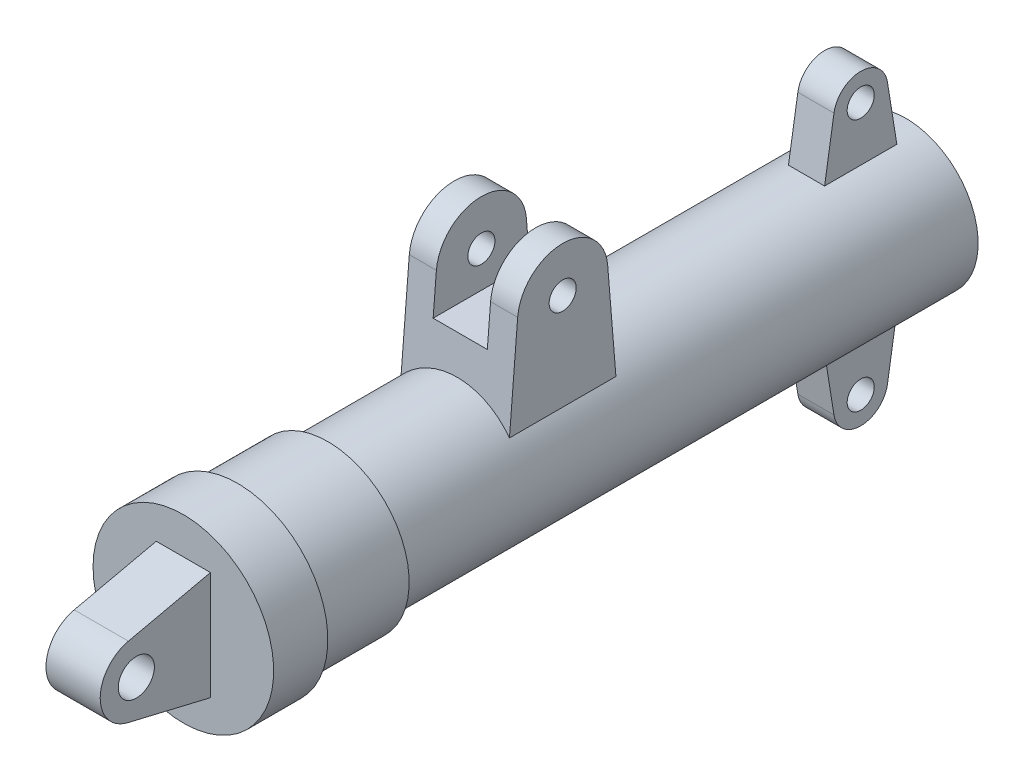
SolidWorks part; units mm, degrees
ref_plane "Front Plane" through (0, 0, 0) normal (1, 0, 0) x (0, 1, 0)
ref_plane "Top Plane" through (0, 0, 0) normal (0, 0, 1) x (0, 1, 0)
ref_plane "Right Plane" through (0, 0, 0) normal (0, 1, 0) x (-1, 0, 0)
sketch "Sketch1" plane through (0, 0, 0) normal (1, 0, 0) x (0, 1, 0)
  line L0 (0, -48.0597) -> (0, 85.8209) construction
  line L1 (0, -48.0597) -> (119.5522, -48.0597) construction
  line L2 (0, 336.9403) -> (0, 351.9403)
  line L3 (0, 351.9403) -> (50, 351.9403)
  line L4 (50, 351.9403) -> (50, 321.9403)
  line L5 (50, 321.9403) -> (45, 321.9403)
  line L6 (45, 321.9403) -> (45, 271.9403)
  line L7 (45, 271.9403) -> (40, 271.9403)
  line L8 (40, 271.9403) -> (40, -48.0597)
  line L9 (40, -48.0597) -> (22.5, -48.0597)
  line L10 (22.5, -48.0597) -> (22.5, -43.0597)
  line L11 (22.5, -43.0597) -> (35, -43.0597)
  line L12 (35, -43.0597) -> (35, 336.9403)
  line L13 (35, 336.9403) -> (0, 336.9403)
  dimension "D1" = 50
  dimension "D2" = 400
  dimension "D3" = 30
  dimension "D4" = 80
  dimension "D5" = 5
  dimension "D6" = 15
  dimension "D7" = 35
  dimension "D8" = 40
  dimension "D9" = 5
  dimension "D10" = 22.5
revolve "Revolve1" add sketch "Sketch1" angle 360 about L2
sketch "Sketch3" plane through (0, 0, 0) normal (1, 0, 0) x (0, 1, 0)
  line L0 (-50, 351.9403) -> (92.7072, 351.9403) construction
  line L1 (0, 310.0004) -> (0, 475.9652) construction
  line L2 (29.6972, 351.9403) -> (-30.3028, 351.9403)
  line L3 (-30.3028, 351.9403) -> (-19.4588, 397.6038)
  line L4 (29.6972, 351.9403) -> (19.5156, 397.3577)
  circle A0 centre (0, 392.9828) radius 10
  arc A1 (19.5156, 397.3577) -> (-19.4588, 397.6038) centre (0, 392.9828) ccw
  point P12 (-0.3028, 351.9403)
  dimension "D1" = 20
  dimension "D2" = 40
  dimension "D3" = 30
extrude "Boss-Extrude1" add sketch "Sketch3" along normal mid plane 30
sketch "Sketch4" plane through (0, 0, 0) normal (1, 0, 0) x (0, 1, 0)
  line L0 (-68.8038, -13.0597) -> (55, -13.0597) construction
  line L1 (0, -61.8196) -> (0, 86.7533) construction
  line L2 (1.3593, -48.0597) -> (76.4747, -48.0597) construction
  line L3 (-40, -48.0597) -> (40, -48.0597) construction
  line L4 (30, -33.0597) -> (30, 6.9403)
  line L5 (30, -33.0597) -> (0, -33.0597) construction
  line L6 (40, -13.0597) -> (40, -18.8653) construction
  line L7 (40, -48.0597) -> (40, 271.9403) construction
  line L8 (40, -13.0597) -> (40, 6.9403) construction
  line L9 (40, 6.9403) -> (40, -33.0597) construction
  line L10 (62.5, -13.0597) -> (95.0236, -13.0597) construction
  line L11 (40, 6.9403) -> (72.374, 1.7512)
  line L12 (40, 6.9403) -> (40, -33.0597)
  line L13 (40, -33.0597) -> (72.374, -27.8707)
  arc A0 (72.374, -27.8707) -> (72.374, 1.7512) centre (70, -13.0597) ccw
  circle A1 centre (70, -13.0597) radius 7.5
  point P14 (30, -13.0597)
  point P20 (0, 0)
  dimension "D1" = 30
  dimension "D7" = 15
  dimension "D2" = 35
  dimension "D3" = 0
  dimension "D4" = 20
  dimension "D5" = 30
  dimension "D6" = 30
extrude "Boss-Extrude3" add sketch "Sketch4" along normal mid plane 20 separate body contours A1 | L13 A0 L11 L12
mirror "Mirror3" about plane through (0, 0, 0) normal (0, 1, 0) of bodies 104
sketch "Sketch6" plane through (0, 0, 0) normal (1, 0, 0) x (0, 1, 0)
  line L0 (-157.5966, 171.9403) -> (80, 171.9403) construction
  line L1 (0, 424.5724) -> (0, -80.0634) construction
  line L2 (-40, 271.9403) -> (40, 271.9403) construction
  line L3 (20, 141.9403) -> (20, 201.9403)
  line L4 (20, 201.9403) -> (82.0416, 196.8568)
  line L5 (20, 141.9403) -> (82.0416, 147.0238)
  arc A0 (82.0416, 147.0238) -> (82.0416, 196.8568) centre (80, 171.9403) ccw
  circle A1 centre (80, 171.9403) radius 7.5
  point P12 (20, 171.9403)
  dimension "D2" = 50
  dimension "D7" = 15
  dimension "D1" = 100
  dimension "D3" = 0
  dimension "D4" = 30
  dimension "D5" = 20
  dimension "D6" = 60
extrude "Boss-Extrude4" add sketch "Sketch6" along normal mid plane 60 contours A1 | L4 A0 L5 L3
sketch "Sketch7" plane through (0, 0, 0) normal (1, 0, 0) x (0, 1, 0)
  line L1 (60, 211.9403) -> (130, 211.9403)
  line L2 (60, 211.9403) -> (60, 131.9403)
  line L3 (60, 131.9403) -> (130, 131.9403)
  line L4 (130, 211.9403) -> (130, 131.9403)
  dimension "D1" = 70
  dimension "D2" = 80
extrude "Cut-Extrude5" cut sketch "Sketch7" against normal mid plane 30 contours L1 L4 L3 L2
